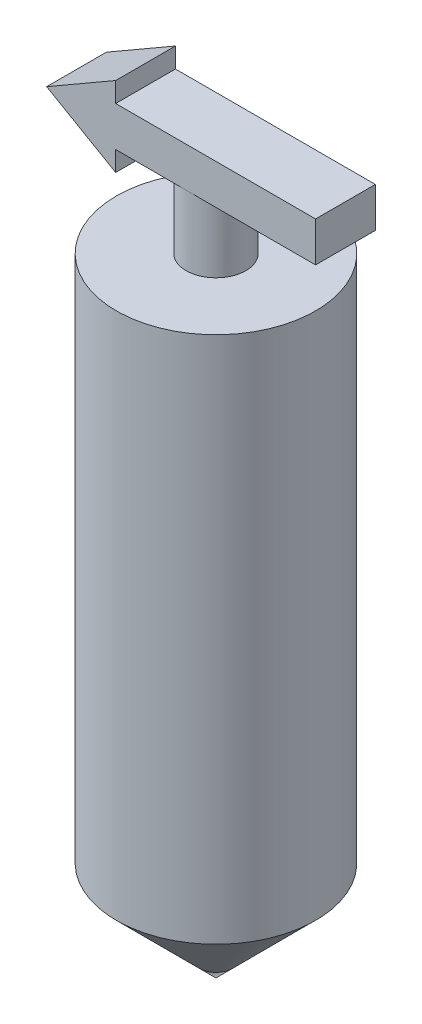
SolidWorks part; units mm, degrees
ref_plane "前视基准面" through (0, 0, 0) normal (0, 0, 1) x (1, 0, 0)
ref_plane "上视基准面" through (0, 0, 0) normal (0, 1, 0) x (1, 0, 0)
ref_plane "右视基准面" through (0, 0, 0) normal (1, 0, 0) x (0, 0, -1)
sketch "草图1" plane through (0, 0, 0) normal (0, 0, 1) x (1, 0, 0)
  line L0 (0, 70) -> (0, 0)
  line L1 (0, 0) -> (10, 10)
  line L2 (10, 10) -> (10, 63)
  line L3 (10, 63) -> (3, 63)
  line L4 (3, 63) -> (3, 70)
  line L5 (3, 70) -> (0, 70)
  point P6 (0, 0)
  dimension "D1" = 70
  dimension "D2" = 3
  dimension "D3" = 7
  dimension "D4" = 45
  dimension "D5" = 7
revolve "旋转1" add sketch "草图1" angle 360 about L0
sketch "草图2" plane through (0, 0, 0) normal (0, 0, 1) x (1, 0, 0)
  line L0 (-14, 72) -> (-7.0718, 68)
  line L1 (-7.0718, 68) -> (-7.0718, 70)
  line L2 (-7.0718, 70) -> (13, 70)
  line L3 (13, 70) -> (13, 74)
  line L4 (13, 72) -> (-14, 72) construction
  line L5 (3, 70) -> (-3, 70) construction
  line L6 (0, 78.6711) -> (0, 65.5284) construction
  line L7 (-7.0718, 74) -> (13, 74)
  line L8 (-7.0718, 76) -> (-7.0718, 74)
  line L9 (-14, 72) -> (-7.0718, 76)
  dimension "D1" = 30
  dimension "D2" = 2
  dimension "D3" = 2
  dimension "D4" = 14
  dimension "D5" = 13
extrude "凸台-拉伸1" add sketch "草图2" along normal mid plane 6
